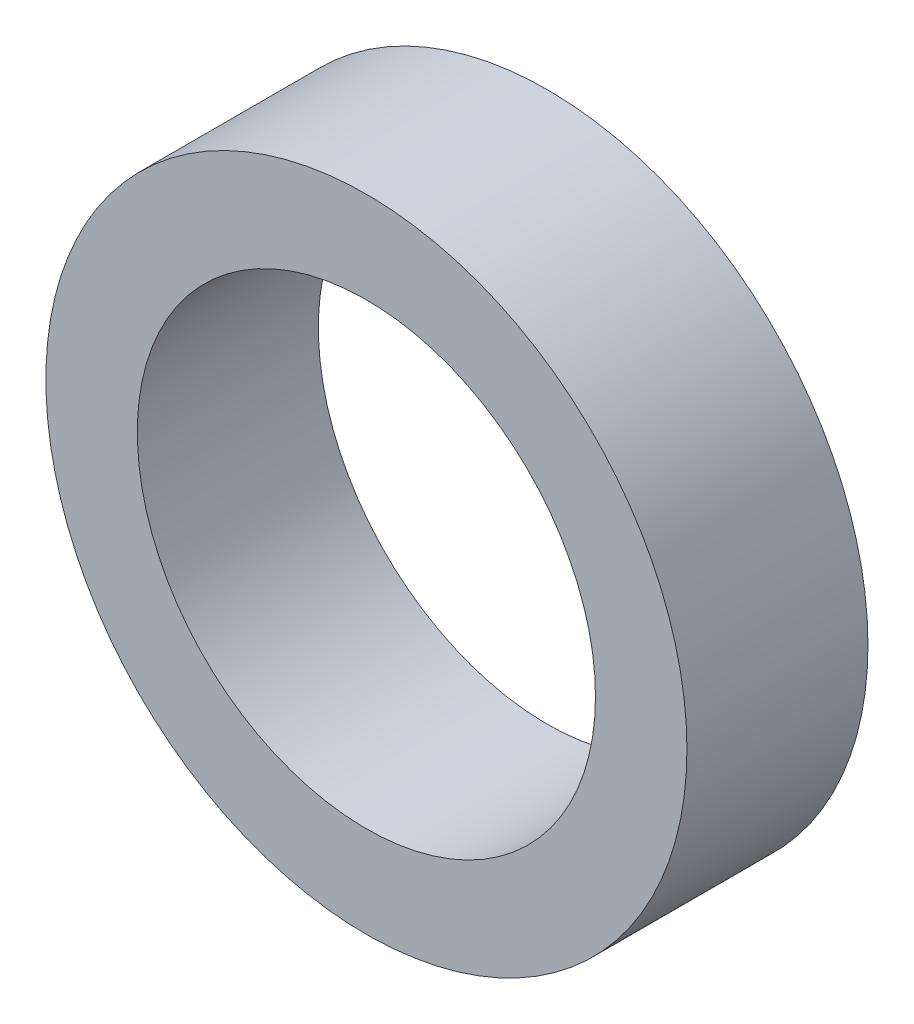
SolidWorks part; units mm, degrees
ref_plane "Front Plane" through (0, 0, 0) normal (0, 0, 1) x (1, 0, 0)
ref_plane "Top Plane" through (0, 0, 0) normal (0, 1, 0) x (1, 0, 0)
ref_plane "Right Plane" through (0, 0, 0) normal (1, 0, 0) x (0, 0, -1)
sketch "S01 - Annular section" plane through (0, 0, 0) normal (0, 0, 1) x (1, 0, 0)
  circle A0 centre (0, 0) radius 8.5
  circle A1 centre (0, 0) radius 6.075
  dimension "D1" = 12.15
  dimension "D2" = 17
extrude "01 - Annular section" add sketch "S01 - Annular section" along normal blind 4.8
